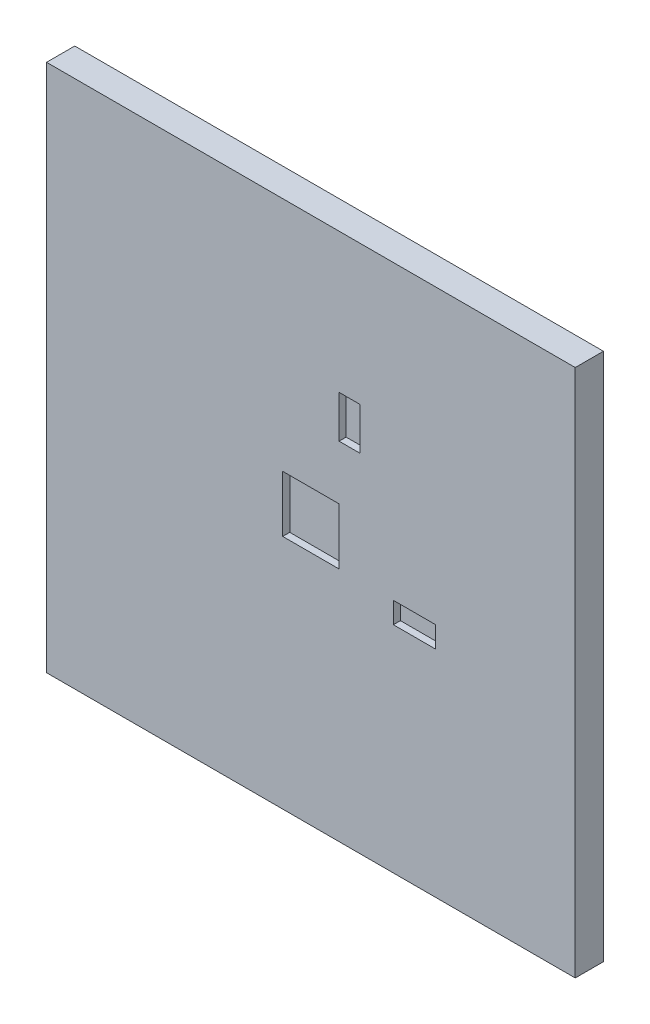
SolidWorks part; units mm, degrees
ref_plane "Front Plane" through (0, 0, 0) normal (0, 0, 1) x (1, 0, 0)
ref_plane "Top Plane" through (0, 0, 0) normal (0, 1, 0) x (1, 0, 0)
ref_plane "Right Plane" through (0, 0, 0) normal (1, 0, 0) x (0, 0, -1)
sketch "Sketch1" plane through (0, 0, 0) normal (0, 0, 1) x (1, 0, 0)
  line L1 (-194.6809, 92.2872) -> (180.3191, 92.2872)
  line L2 (-194.6809, 92.2872) -> (-194.6809, -282.7128)
  line L3 (-194.6809, -282.7128) -> (180.3191, -282.7128)
  line L4 (180.3191, 92.2872) -> (180.3191, -282.7128)
  dimension "D1" = 375
  dimension "D2" = 375
extrude "Boss-Extrude1" add sketch "Sketch1" along normal blind 20 contours L2 L1 L4 L3
sketch "Sketch2" plane through (0, 0, 20) normal (0, 0, 1) x (1, 0, 0)
  line L0 (-194.6809, -282.7128) -> (180.3191, -282.7128) construction
  line L1 (-27.1809, -75.2128) -> (12.8191, -75.2128)
  line L2 (-27.1809, -75.2128) -> (-27.1809, -115.2128)
  line L3 (-27.1809, -115.2128) -> (12.8191, -115.2128)
  line L4 (12.8191, -75.2128) -> (12.8191, -115.2128)
  line L5 (12.8191, -6.7128) -> (27.8191, -6.7128)
  line L6 (12.8191, -6.7128) -> (12.8191, -36.7128)
  line L7 (12.8191, -36.7128) -> (27.8191, -36.7128)
  line L8 (27.8191, -6.7128) -> (27.8191, -36.7128)
  line L9 (51.3191, -115.2128) -> (81.3191, -115.2128)
  line L10 (51.3191, -115.2128) -> (51.3191, -130.2128)
  line L11 (51.3191, -130.2128) -> (81.3191, -130.2128)
  line L12 (81.3191, -115.2128) -> (81.3191, -130.2128)
  line L13 (-194.6809, 92.2872) -> (-194.6809, -282.7128) construction
  line L14 (180.3191, 92.2872) -> (180.3191, -282.7128) construction
  line L15 (-194.6809, 92.2872) -> (180.3191, 92.2872) construction
  dimension "D1" = 40
  dimension "D2" = 40
  dimension "D3" = 167.5
  dimension "D4" = 167.5
  dimension "D5" = 129
  dimension "D6" = 30
  dimension "D7" = 15
  dimension "D8" = 129
  dimension "D9" = 30
  dimension "D10" = 15
extrude "Cut-Extrude1" cut sketch "Sketch2" against normal blind 5 contours L8 L5 L6 L7 | L12 L9 L10 L11 | L2 L1 L4 L3
